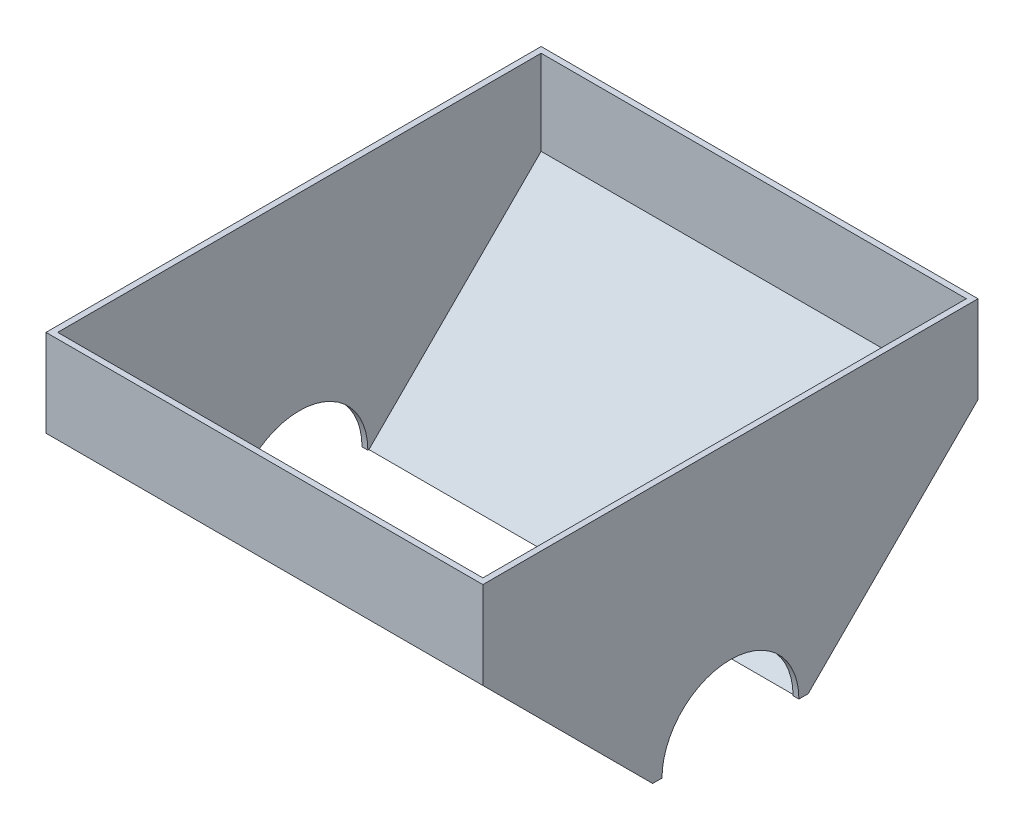
SolidWorks part; units mm, degrees
ref_plane "前视基准面" through (0, 0, 0) normal (0, 0, 1) x (1, 0, 0)
ref_plane "上视基准面" through (0, 0, 0) normal (0, 1, 0) x (1, 0, 0)
ref_plane "右视基准面" through (0, 0, 0) normal (1, 0, 0) x (0, 0, -1)
other "Configuration Table"
sketch "草图1" plane through (0, 0, 0) normal (1, 0, 0) x (0, 0, -1)
  line L0 (0, 0) -> (85, 0)
  line L1 (85, 0) -> (85, -30)
  line L2 (85, -30) -> (26.7047, -88.2953)
  line L3 (0, 0) -> (-85, 0)
  line L4 (-85, 0) -> (-85, -30)
  line L5 (-85, -30) -> (-26.7047, -88.2953)
  line L6 (-26.7047, -88.2953) -> (26.7047, -88.2953)
  dimension "D1" = 85
  dimension "D2" = 85
  dimension "D3" = 30
  dimension "D4" = 45
  dimension "D5" = 45
  dimension "D6" = 30
extrude "凸台-拉伸1" add sketch "草图1" along normal mid plane 150
shell "抽壳1" thickness 2
sketch "草图2" plane through (75, 0, 0) normal (1, 0, 0) x (0, 0, -1)
  line L0 (-26.7047, -88.2953) -> (26.7047, -88.2953) construction
  circle A0 centre (0, -88.2953) radius 23.5
  dimension "D1" = 47
extrude "切除-拉伸1" cut sketch "草图2" against normal through all
